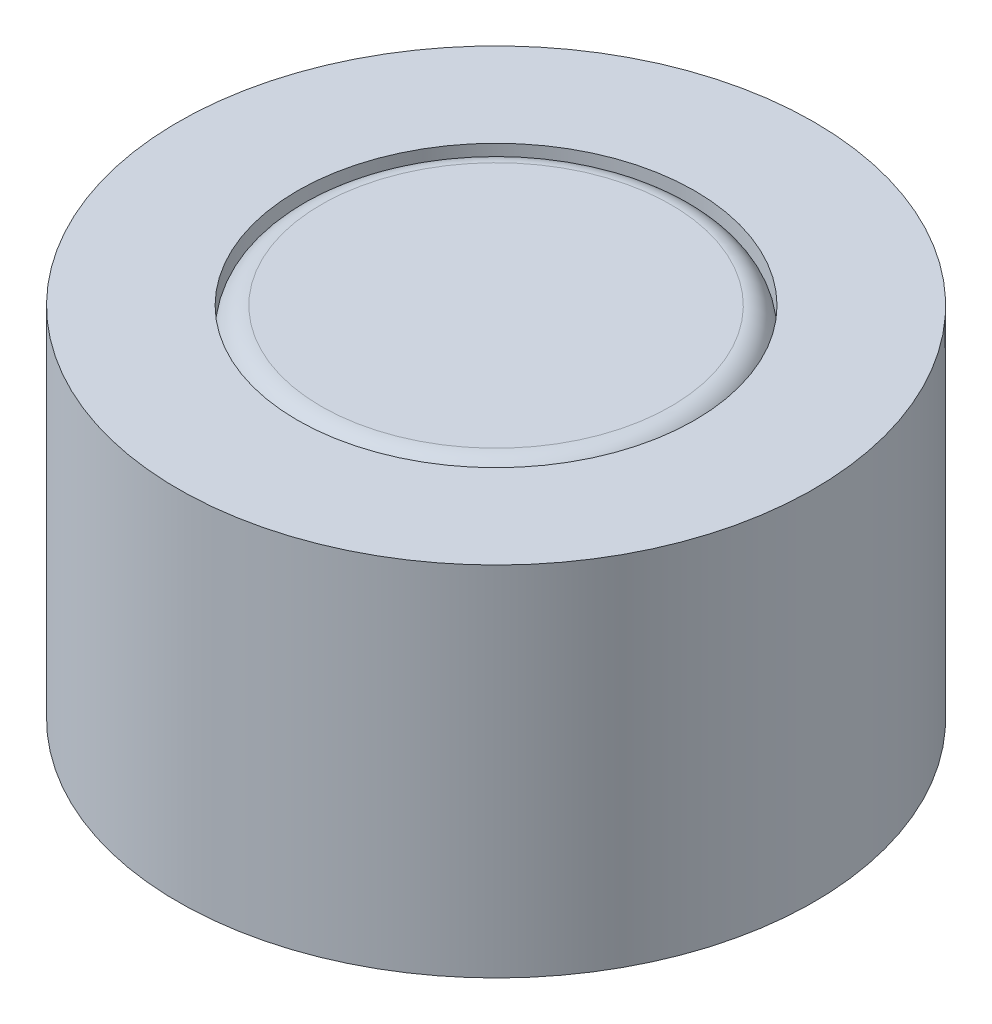
SolidWorks part; units mm, degrees
other "磁钢-5-3"
ref_plane "前视基准面" through (0, 0, 0) normal (0, 0, 1) x (1, 0, 0)
ref_plane "上视基准面" through (0, 0, 0) normal (0, 1, 0) x (1, 0, 0)
ref_plane "右视基准面" through (0, 0, 0) normal (1, 0, 0) x (0, 0, -1)
sketch "草图1" plane through (0, 0, 0) normal (0, 0, 1) x (1, 0, 0)
  line L0 (0, 0) -> (0, 8.77) construction
  line L1 (0, 0) -> (6.482, 0) construction
  line L2 (2.025, 0) -> (2.025, 1.5)
  line L4 (2.025, 0) -> (4, 0)
  line L5 (4, 0) -> (4, 4.5)
  line L6 (4, 4.5) -> (2.5, 4.5)
  line L7 (2.5, 4.5) -> (2.5, 1.5)
  line L10 (2.5, 1.5) -> (2.025, 1.5)
  dimension "D1" = 1.5
  dimension "D2" = 4.05
  dimension "D3" = 5
  dimension "D4" = 3
  dimension "D5" = 8
revolve "旋转1" add sketch "草图1" angle 360 about L0
sketch "草图2" plane through (0, 0, 0) normal (0, 0, 1) x (1, 0, 0)
  line L0 (0, 0) -> (0, 5.3553) construction
  line L1 (-4, 0) -> (4, 0) construction
  line L3 (0, 4.5) -> (2.5, 4.5)
  line L4 (0, 4.5) -> (0, 1.5)
  line L5 (0, 1.5) -> (2.5, 1.5)
  line L6 (2.5, 4.5) -> (2.5, 1.5)
  dimension "D1" = 1.5
  dimension "D2" = 3
  dimension "D3" = 2.5
revolve "旋转2" add sketch "草图2" angle 360 about L0
fillet "圆角1" radius 0.3 2 edges at (0, 1.5, -2.5) (0, 4.5, -2.5)
pattern_linear "阵列(线性)1" [suppressed] count 3 spacing 18 count 2 spacing 13
sketch "草图3" [suppressed] plane through (0, 0, 0) normal (0, -1, 0) x (1, 0, 0)
  circle A1 centre (0, 0) radius 1.99
  circle A2 centre (0, 0) radius 1.99
  circle A3 centre (0, 36) radius 1.99
  circle A4 centre (0, 36) radius 1.99
  circle A5 centre (0, 18) radius 1.99
  circle A6 centre (0, 18) radius 1.99
  circle A9 centre (-13, 36) radius 1.99 construction
  circle A10 centre (-13, 18) radius 1.99 construction
  circle A11 centre (-13, 0) radius 1.99 construction
  circle A15 centre (-13, 36) radius 1.99
  circle A16 centre (-13, 18) radius 1.99
  circle A17 centre (-13, 0) radius 1.99
  dimension "D1" = 0
  dimension "D2" = 0
  dimension "D3" = 0
sketch "草图4" [suppressed] plane through (0, 1.5, 0) normal (0, 1, 0) x (1, 0, 0)
  circle A0 centre (-13, -36) radius 2.5 construction
  circle A1 centre (0, -36) radius 2.5 construction
  circle A2 centre (0, -18) radius 2.5 construction
  circle A3 centre (0, 0) radius 2.5 construction
  circle A4 centre (-13, 0) radius 2.5 construction
  circle A5 centre (-13, -18) radius 2.5 construction
  circle A6 centre (-13, -36) radius 2.5
  circle A7 centre (0, -36) radius 2.5
  circle A8 centre (0, -18) radius 2.5
  circle A9 centre (0, 0) radius 2.5
  circle A10 centre (-13, 0) radius 2.5
  circle A11 centre (-13, -18) radius 2.5
sketch "草图5" [suppressed] plane through (0, 0, 0) normal (0, -1, 0) x (1, 0, 0)
  circle A0 centre (-13, 0) radius 4 construction
  circle A1 centre (0, 0) radius 4 construction
  circle A2 centre (0, 18) radius 4 construction
  circle A3 centre (0, 36) radius 4 construction
  circle A4 centre (-13, 36) radius 4 construction
  circle A5 centre (-13, 18) radius 4 construction
  circle A6 centre (-13, 0) radius 4
  circle A7 centre (0, 0) radius 4
  circle A8 centre (0, 18) radius 4
  circle A9 centre (0, 36) radius 4
  circle A10 centre (-13, 36) radius 4
  circle A11 centre (-13, 18) radius 4
sketch "草图6" [suppressed] plane through (0, 0, 0) normal (0, -1, 0) x (1, 0, 0)
  line L1 (0, 18) -> (-13, 18) construction
  line L2 (-6.5, 18) -> (-6.5, 50.1921) construction
  line L3 (-23, 48) -> (10, 48)
  line L4 (-23, 48) -> (-23, -12)
  line L5 (-23, -12) -> (10, -12)
  line L6 (10, 48) -> (10, -12)
  dimension "D1" = 33
  dimension "D2" = 60
